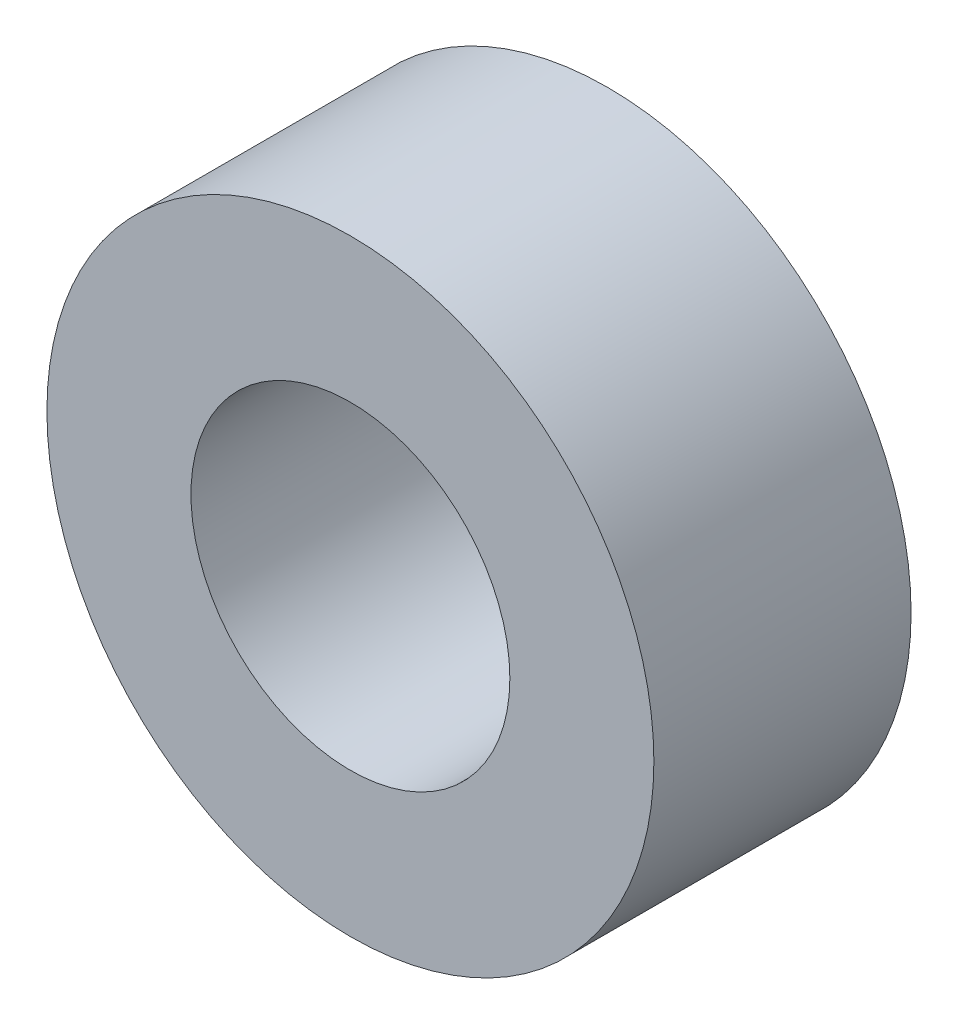
SolidWorks part; units mm, degrees
ref_plane "Front Plane" through (0, 0, 0) normal (0, 0, 1) x (1, 0, 0)
ref_plane "Top Plane" through (0, 0, 0) normal (0, 1, 0) x (1, 0, 0)
ref_plane "Right Plane" through (0, 0, 0) normal (1, 0, 0) x (0, 0, -1)
sketch "Sketch1" plane through (0, 0, 0) normal (0, 0, 1) x (1, 0, 0)
  circle A0 centre (0, 0) radius 5.9
  circle A1 centre (0, 0) radius 3.1
extrude "Boss-Extrude1" add sketch "Sketch1" along normal blind 5
